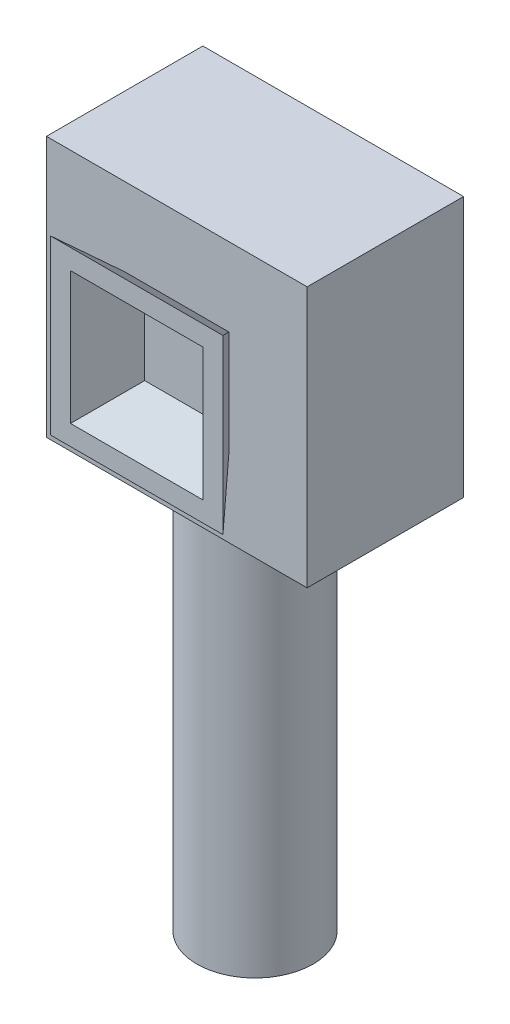
SolidWorks part; units mm, degrees
ref_plane "Ön Düzlem" through (0, 0, 0) normal (0, 0, 1) x (1, 0, 0)
ref_plane "Üst Düzlem" through (0, 0, 0) normal (0, 1, 0) x (1, 0, 0)
ref_plane "Sağ Düzlem" through (0, 0, 0) normal (1, 0, 0) x (0, 0, -1)
sketch "Çizim2" plane through (0, 0, 0) normal (0, 0, 1) x (1, 0, 0)
  line L0 (21.5, 0) -> (8, 0)
  line L1 (-21.5, 21.5) -> (21.5, 21.5)
  line L2 (-21.5, 21.5) -> (-21.5, -21.5)
  line L3 (-21.5, -21.5) -> (21.5, -21.5)
  line L4 (21.5, 21.5) -> (21.5, -21.5)
  line L5 (-16.5, 16.5) -> (16.5, 16.5)
  line L6 (-16.5, 16.5) -> (-16.5, -16.5)
  line L7 (-16.5, -16.5) -> (16.5, -16.5)
  line L8 (16.5, 16.5) -> (16.5, -16.5)
  line L9 (-21.5, 0) -> (-8, 0)
  line L10 (0, 21.5) -> (0, 8)
  line L11 (0, -21.5) -> (0, -8)
  line L12 (0, -8) -> (8, -8)
  line L13 (8, -8) -> (8, 0)
  line L14 (8, 8) -> (0, 8)
  line L15 (-8, 8) -> (-8, 0)
  line L16 (-8, -8) -> (0, -8)
  line L17 (-8, -8) -> (-8, 0)
  line L18 (-8, 8) -> (0, 8)
  line L19 (8, 8) -> (8, 0)
  dimension "D1" = 43
  dimension "D2" = 43
  dimension "D3" = 33
  dimension "D4" = 33
extrude "Yükseklik-Ekstrüzyon1" add sketch "Çizim2" along normal blind 10 contours L10 L1 L2 L9 L6 L5 | L15 L18 L10 L5 L6 L9 | L3 L11 L7 L6 L9 L2 | L16 L17 L9 L6 L7 L11 | L11 L3 L4 L0 L8 L7 | L13 L12 L11 L7 L8 L0 | L14 L19 L0 L8 L5 L10 | L1 L10 L5 L8 L0 L4
sketch "Çizim3" plane through (0, 0, 10) normal (0, 0, 1) x (1, 0, 0)
  line L1 (-21.5, 21.5) -> (21.5, 21.5)
  line L2 (-21.5, 21.5) -> (-21.5, -21.5)
  line L3 (-21.5, -21.5) -> (21.5, -21.5)
  line L4 (21.5, 21.5) -> (21.5, -21.5)
  line L5 (-16.5, 16.5) -> (16.5, 16.5)
  line L6 (-16.5, 16.5) -> (-16.5, -16.5)
  line L7 (-16.5, -16.5) -> (16.5, -16.5)
  line L8 (16.5, 16.5) -> (16.5, -16.5)
  dimension "D1" = 33
  dimension "D2" = 33
extrude "Kes-Ekstrüzyon1" cut sketch "Çizim3" against normal up to surface (10 mm away) draft 40.365 contours L6 L5 L8 L7
sketch "Çizim7" plane through (0, 21.5, 0) normal (0, 1, 0) x (1, 0, 0)
  line L1 (-21.5, -10) -> (21.5, -10)
  line L4 (-13, 0) -> (13, 0)
  line L5 (-21.5, -10) -> (-13, 0)
  line L6 (13, 0) -> (21.5, -10)
extrude "Kes-Ekstrüzyon6" cut sketch "Çizim7" against normal blind 56 flip side to cut
sketch "Çizim10" plane through (0, 0, 0) normal (1, 0, 0) x (0, 0, -1)
  line L0 (-10, 21.5) -> (-10, -21.5)
  line L1 (0, 13) -> (0, -13)
  line L2 (-10, 21.5) -> (0, 13)
  line L3 (0, -13) -> (-10, -21.5)
extrude "Kes-Ekstrüzyon8" cut sketch "Çizim10" against normal mid plane 56 flip side to cut
sketch "Çizim11" plane through (0, 0, 0) normal (0, 0, -1) x (-1, 0, 0)
  line L0 (-32.5, -32.5) -> (32.5, 32.5)
  line L1 (-32.5, 32.5) -> (32.5, 32.5)
  line L2 (-32.5, 32.5) -> (-32.5, -32.5)
  line L3 (-32.5, -32.5) -> (32.5, -32.5)
  line L4 (32.5, 32.5) -> (32.5, -32.5)
  line M5 (-8, -8) -> (-8, 8)
  line M6 (-8, 8) -> (8, 8)
  line M7 (8, 8) -> (8, -8)
  line M8 (8, -8) -> (-8, -8)
  line M9 (13, 13) -> (-13, 13)
  line M10 (-13, 13) -> (-13, -13)
  line M11 (-13, -13) -> (13, -13)
  line M12 (13, -13) -> (13, 13)
  dimension "D1" = 65
  dimension "D2" = 65
extrude "Yükseklik-Ekstrüzyon2" add sketch "Çizim11" along normal blind 39 contours L4 L0 L3 M12 M11 | L1 L2 L0 M10 M9 | L0 M10 M5 M6 M9 | L0 M5 M6 | L0 M8 M7 | L0 M11 M12 M7 M8
sketch "Çizim12" plane through (0, -32.5, 0) normal (0, -1, 0) x (1, 0, 0)
  circle A0 centre (0, -19.5) radius 14.5
extrude "Yükseklik-Ekstrüzyon3" add sketch "Çizim12" along normal blind 100
sketch "Çizim13" plane through (0, -132.5, 0) normal (0, -1, 0) x (1, 0, 0)
  line L7 (-1, -31.8809) -> (1, -31.8809)
  line L8 (-1, -31.8809) -> (0, -33.6529)
  line L9 (0, -33.6529) -> (1, -31.8809)
  line L10 (-3.663, -33.1706) -> (-2.2385, -31.7179)
  line L11 (-4.1703, -31.2002) -> (-2.2385, -31.7179)
  line L12 (-4.1703, -31.2002) -> (-3.663, -33.1706)
  line L13 (-7.0764, -31.7568) -> (-5.3244, -30.7222)
  line L14 (-7.0565, -29.7222) -> (-5.3244, -30.7222)
  line L15 (-7.0565, -29.7222) -> (-7.0764, -31.7568)
  line L16 (-10.0076, -29.5076) -> (-8.0475, -28.9617)
  line L17 (-9.4617, -27.5475) -> (-8.0475, -28.9617)
  line L18 (-9.4617, -27.5475) -> (-10.0076, -29.5076)
  line L19 (-12.2568, -26.5764) -> (-10.2222, -26.5565)
  line L20 (-11.2222, -24.8244) -> (-10.2222, -26.5565)
  line L21 (-11.2222, -24.8244) -> (-12.2568, -26.5764)
  line L22 (-13.6706, -23.163) -> (-11.7002, -23.6703)
  line L23 (-12.2179, -21.7385) -> (-11.7002, -23.6703)
  line L24 (-12.2179, -21.7385) -> (-13.6706, -23.163)
  line L25 (-14.1529, -19.5) -> (-12.3809, -20.5)
  line L26 (-12.3809, -18.5) -> (-12.3809, -20.5)
  line L27 (-12.3809, -18.5) -> (-14.1529, -19.5)
  line L80 (-12.2568, -12.4236) -> (-11.2222, -14.1756) [skipped]
  line L81 (-10.2222, -12.4435) -> (-11.2222, -14.1756) [skipped]
  line L82 (-10.2222, -12.4435) -> (-12.2568, -12.4236) [skipped]
  line L83 (-8.0475, -10.0383) -> (-10.0076, -9.4924) [skipped]
  line L84 (-10.0076, -9.4924) -> (-9.4617, -11.4525) [skipped]
  line L85 (-8.0475, -10.0383) -> (-9.4617, -11.4525) [skipped]
  line L86 (-7.0764, -7.2432) -> (-7.0565, -9.2778) [skipped]
  line L87 (-5.3244, -8.2778) -> (-7.0565, -9.2778) [skipped]
  line L88 (-5.3244, -8.2778) -> (-7.0764, -7.2432) [skipped]
  line L89 (-3.663, -5.8294) -> (-4.1703, -7.7998) [skipped]
  line L90 (10.0076, -9.4924) -> (8.0475, -10.0383) [skipped]
  line L91 (9.4617, -11.4525) -> (8.0475, -10.0383) [skipped]
  line L92 (9.4617, -11.4525) -> (10.0076, -9.4924) [skipped]
  line L93 (12.2568, -12.4236) -> (10.2222, -12.4435) [skipped]
  line L94 (11.2222, -14.1756) -> (10.2222, -12.4435) [skipped]
  line L95 (11.2222, -14.1756) -> (12.2568, -12.4236) [skipped]
  line L96 (13.6706, -15.837) -> (11.7002, -15.3297) [skipped]
  line L97 (14.1529, -19.5) -> (12.3809, -18.5) [skipped]
  line L98 (12.3809, -20.5) -> (12.3809, -18.5) [skipped]
  line L99 (12.3809, -20.5) -> (14.1529, -19.5) [skipped]
  line L100 (10.0076, -29.5076) -> (9.4617, -27.5475) [skipped]
  line L101 (8.0475, -28.9617) -> (9.4617, -27.5475) [skipped]
  line L102 (8.0475, -28.9617) -> (10.0076, -29.5076) [skipped]
  line L103 (7.0764, -31.7568) -> (7.0565, -29.7222) [skipped]
  line L104 (5.3244, -30.7222) -> (7.0565, -29.7222) [skipped]
  line L105 (5.3244, -30.7222) -> (7.0764, -31.7568) [skipped]
  line L106 (3.663, -33.1706) -> (4.1703, -31.2002) [skipped]
  line L107 (2.2385, -31.7179) -> (4.1703, -31.2002) [skipped]
  line L108 (2.2385, -31.7179) -> (3.663, -33.1706) [skipped]
  line L109 (12.2568, -26.5764) -> (11.2222, -24.8244) [skipped]
  line L110 (10.2222, -26.5565) -> (11.2222, -24.8244) [skipped]
  line L111 (10.2222, -26.5565) -> (12.2568, -26.5764) [skipped]
  line L112 (13.6706, -23.163) -> (12.2179, -21.7385) [skipped]
  line L113 (11.7002, -23.6703) -> (12.2179, -21.7385) [skipped]
  line L114 (11.7002, -23.6703) -> (13.6706, -23.163) [skipped]
  line L115 (12.2179, -17.2615) -> (11.7002, -15.3297) [skipped]
  line L116 (12.2179, -17.2615) -> (13.6706, -15.837) [skipped]
  line L117 (7.0764, -7.2432) -> (5.3244, -8.2778) [skipped]
  line L118 (7.0565, -9.2778) -> (5.3244, -8.2778) [skipped]
  line L119 (7.0565, -9.2778) -> (7.0764, -7.2432) [skipped]
  line L120 (3.663, -5.8294) -> (2.2385, -7.2821) [skipped]
  line L121 (4.1703, -7.7998) -> (2.2385, -7.2821) [skipped]
  line L122 (4.1703, -7.7998) -> (3.663, -5.8294) [skipped]
  line L123 (0, -5.3471) -> (-1, -7.1191) [skipped]
  line L124 (1, -7.1191) -> (-1, -7.1191) [skipped]
  line L125 (1, -7.1191) -> (0, -5.3471) [skipped]
  line L126 (-2.2385, -7.2821) -> (-4.1703, -7.7998) [skipped]
  line L127 (-2.2385, -7.2821) -> (-3.663, -5.8294) [skipped]
  line L128 (-11.7002, -15.3297) -> (-12.2179, -17.2615) [skipped]
  line L129 (-13.6706, -15.837) -> (-12.2179, -17.2615) [skipped]
  line L130 (-11.7002, -15.3297) -> (-13.6706, -15.837) [skipped]
  dimension "D1" = 24
extrude "Yükseklik-Ekstrüzyon4" add sketch "Çizim13" along normal blind 2
